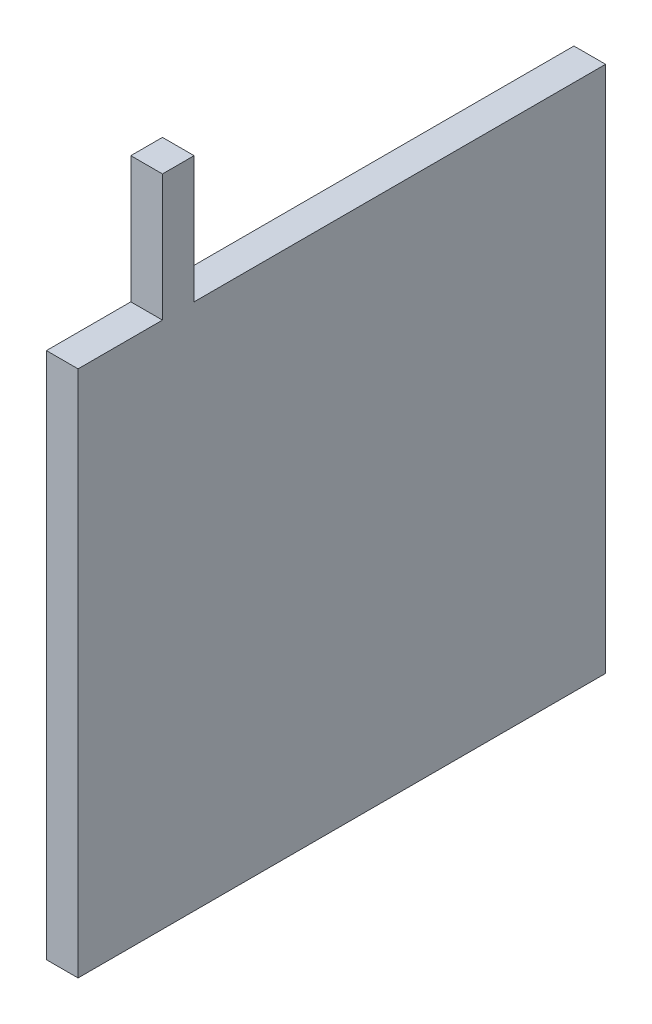
SolidWorks part; units mm, degrees
ref_plane "Front Plane" through (0, 0, 0) normal (0, 0, 1) x (1, 0, 0)
ref_plane "Top Plane" through (0, 0, 0) normal (0, 1, 0) x (1, 0, 0)
ref_plane "Right Plane" through (0, 0, 0) normal (1, 0, 0) x (0, 0, -1)
sketch "Sketch1" plane through (0, 0, 0) normal (1, 0, 0) x (0, 0, -1)
  line L0 (0, 0) -> (0, -12)
  line L1 (0, -12) -> (-8, -12)
  line L2 (-8, -12) -> (-8, -62)
  line L3 (-8, -62) -> (42, -62)
  line L4 (42, -62) -> (42, -12)
  line L5 (42, -12) -> (3, -12)
  line L6 (3, -12) -> (3, 0)
  line L7 (3, 0) -> (0, 0)
  point P10 (0, 0)
  dimension "D1" = 50
  dimension "D2" = 50
  dimension "D3" = 3
  dimension "D4" = 8
  dimension "D5" = 12
extrude "Boss-Extrude1" add sketch "Sketch1" along normal blind 3
